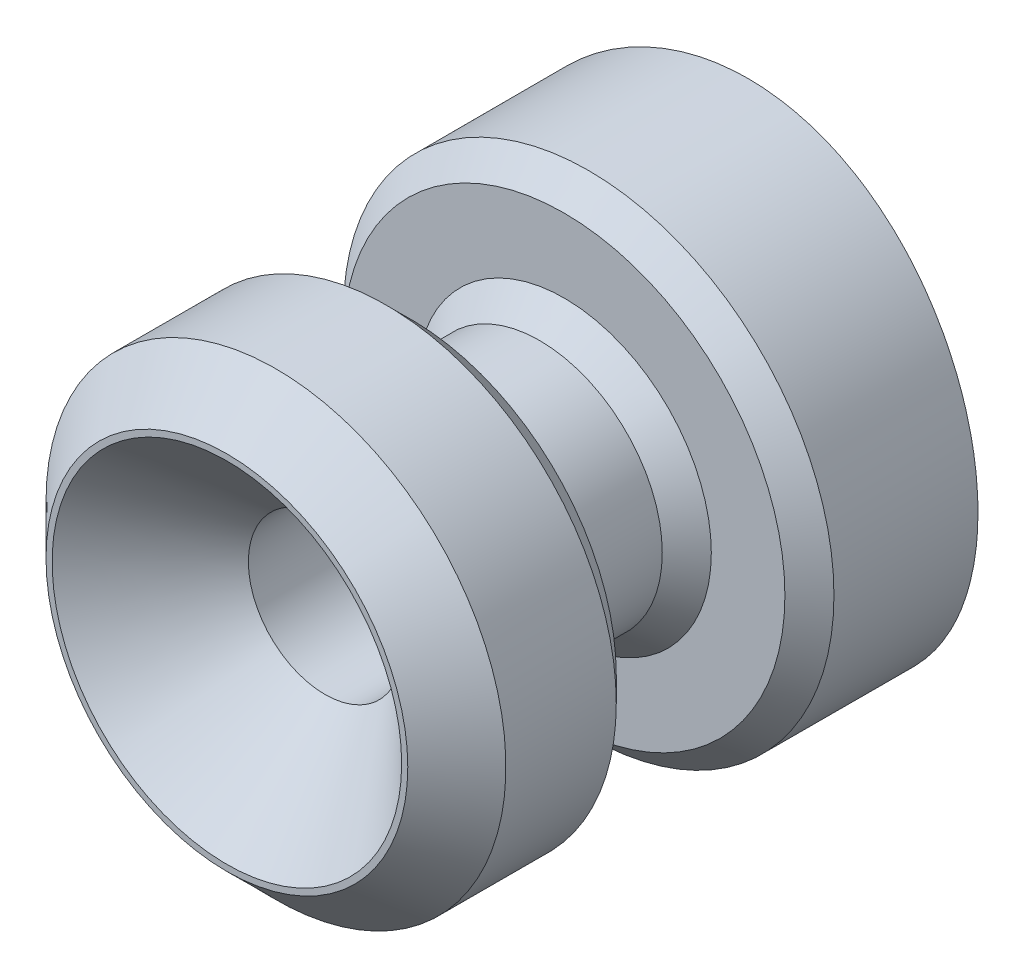
SolidWorks part; units mm, degrees
ref_plane "Front Plane" through (0, 0, 0) normal (0, 0, 1) x (1, 0, 0)
ref_plane "Top Plane" through (0, 0, 0) normal (0, 1, 0) x (1, 0, 0)
ref_plane "Right Plane" through (0, 0, 0) normal (1, 0, 0) x (0, 0, -1)
sketch "Sketch1" plane through (0, 0, 0) normal (0, 0, 1) x (1, 0, 0)
  circle A0 centre (0, 0) radius 5.08
  circle A1 centre (0, 0) radius 1.5875
  dimension "D1" = 10.16
  dimension "D2" = 3.175
extrude "Boss-Extrude1" add sketch "Sketch1" along normal blind 3.81
sketch "Sketch2" plane through (0, 0, 3.81) normal (0, 0, 1) x (1, 0, 0)
  circle A0 centre (0, 0) radius 1.5875
  circle A1 centre (0, 0) radius 2.54
  dimension "D1" = 5.08
  dimension "D2" = 3.175
extrude "Boss-Extrude2" add sketch "Sketch2" along normal blind 3.175
sketch "Sketch3" plane through (0, 0, 6.985) normal (0, 0, 1) x (1, 0, 0)
  circle A0 centre (0, 0) radius 1.5875
  circle A1 centre (0, 0) radius 4.7625
  circle A2 centre (0, 0) radius 1.5875 construction
  dimension "D1" = 9.525
extrude "Boss-Extrude3" add sketch "Sketch3" along normal blind 3.81
chamfer "Chamfer1" distance 0.508 angle 45 2 edges at (2.54, 0, 3.81) (2.54, 0, 6.985)
chamfer "Chamfer2" distance 0.508 angle 45 2 edges at (5.08, 0, 3.81) (4.7625, 0, 6.985)
chamfer "Chamfer3" distance 2.032 angle 45 1 edges at (1.5875, 0, 10.795)
sketch "Sketch4" plane through (0, 0, 0) normal (1, 0, 0) x (0, 0, -1)
  circle A0 centre (40.3212, 0) radius 40.64
  dimension "D1" = 81.28
extrude "Cut-Extrude1" cut sketch "Sketch4" against normal through all both and the other way through all
chamfer "Chamfer4" distance 1.016 angle 45 1 edges at (4.7625, 0, 10.795)
